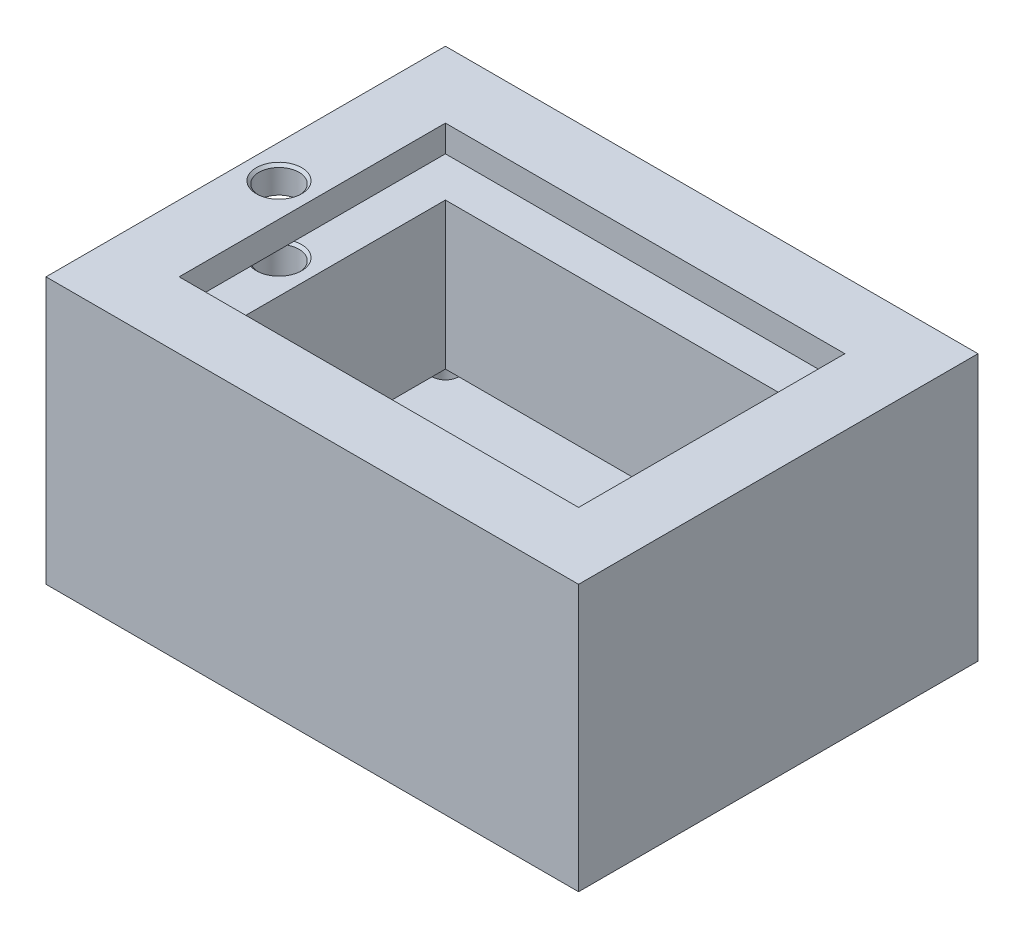
SolidWorks part; units mm, degrees
ref_plane "Front Plane" through (0, 0, 0) normal (0, 0, 1) x (1, 0, 0)
ref_plane "Top Plane" through (0, 0, 0) normal (0, 1, 0) x (1, 0, 0)
ref_plane "Right Plane" through (0, 0, 0) normal (1, 0, 0) x (0, 0, -1)
sketch "Sketch1" plane through (0, 0, 0) normal (0, 1, 0) x (1, 0, 0)
  line L1 (-25.4, -19.05) -> (25.4, -19.05)
  line L2 (-25.4, -19.05) -> (-25.4, 19.05)
  line L3 (-25.4, 19.05) -> (25.4, 19.05)
  line L4 (25.4, -19.05) -> (25.4, 19.05)
  line L5 (-25.4, -19.05) -> (25.4, 19.05) construction
  line L6 (-25.4, 19.05) -> (25.4, -19.05) construction
  point P0 (0, 0)
  dimension "D1" = 50.8
  dimension "D2" = 38.1
extrude "Boss-Extrude1" add sketch "Sketch1" along normal blind 25.4
sketch "Sketch2" plane through (0, 25.4, 0) normal (0, 1, 0) x (1, 0, 0)
  line L0 (25.4, 19.05) -> (-25.4, 19.05) construction
  line L1 (-19.05, -12.7) -> (19.05, -12.7)
  line L2 (-19.05, -12.7) -> (-19.05, 12.7)
  line L3 (-19.05, 12.7) -> (19.05, 12.7)
  line L4 (19.05, -12.7) -> (19.05, 12.7)
  line L5 (-19.05, -12.7) -> (19.05, 12.7) construction
  line L6 (-19.05, 12.7) -> (19.05, -12.7) construction
  line L8 (25.4, -19.05) -> (25.4, 19.05) construction
  point P0 (0, 0)
  dimension "D1" = 6.35
  dimension "D2" = 6.35
extrude "Cut-Extrude1" cut sketch "Sketch2" against normal blind 20.32
sketch "Sketch4" plane through (-25.4, 0, 0) normal (-1, 0, 0) x (0, 0, 1)
  line L0 (-16.5176, 22.86) -> (16.5176, 22.86)
  line L1 (16.5176, 22.86) -> (16.5176, 19.0424)
  line L2 (16.5176, 19.0424) -> (-16.5176, 19.0424)
  line L3 (-16.5176, 19.0424) -> (-16.5176, 22.86)
  line L5 (-19.05, 25.4) -> (19.05, 25.4) construction
  point P6 (0, 25.4)
  point P7 (0, 22.86)
  dimension "D1" = 33.0352
  dimension "D2" = 3.8176
  dimension "D3" = 2.54
extrude "Cut-Extrude2" cut sketch "Sketch4" against normal blind 48.2752
sketch "Sketch5" plane through (0, 25.4, 0) normal (0, 1, 0) x (1, 0, 0)
  line L0 (-19.05, 0) -> (-25.4, 0) construction
  line L1 (-19.05, 12.7) -> (-19.05, -12.7) construction
  line L2 (-25.4, 19.05) -> (-25.4, -19.05) construction
  circle A0 centre (-22.225, 0) radius 1.9088
  dimension "D1" = 3.8176
extrude "Cut-Extrude3" cut sketch "Sketch5" against normal blind 10.16
chamfer "Chamfer1" distance 0.254 angle 45 1 edges at (-22.225, 25.4, 1.9088)
chamfer "Chamfer2" distance 0.254 angle 45 1 edges at (-22.225, 19.0424, -1.9088)
sketch "Sketch15" plane through (0, 5.08, 0) normal (0, 1, 0) x (1, 0, 0)
  circle A0 centre (-19.05, 12.7) radius 1.27
  circle A1 centre (19.05, 12.7) radius 1.27
  circle A2 centre (-19.05, -12.7) radius 1.27
  circle A3 centre (19.05, -12.7) radius 1.27
  dimension "D1" = 2.54
  dimension "D2" = 2.54
  dimension "D3" = 2.54
  dimension "D4" = 2.54
extrude "Cut-Extrude4" cut sketch "Sketch15" against normal up to next
equation "\"L\"= 2'Box Length [in]"
equation "\"W\"= 1.5'Box Width [in]"
equation "\"D1@Sketch1\"=\"L\""
equation "\"D2@Sketch1\"=\"W\""
equation "\"H\"= 1'Box Height {in}"
equation "\"SW\"= 1.3 + 0.0006'Slide Width gap [in]"
equation "\"SL\"= 1.9 + 0.0006'Slide Length Gap [in]"
equation "\"D1@Sketch4\"=\"SW\""
equation "\"SH\"= 0.15 + 0.0003'Slide Height Gap [in]"
equation "\"D2@Sketch4\"=\"SH\""
equation "\"D1@Cut-Extrude2\"=\"SL\""
equation "\"Hole\"= 0.15 + 0.0003'Hole Radius [in]"
equation "\"D1@Sketch5\"=\"Hole\""
equation "\"Hole Depth\"= 0.4'Hole Depth [in]"
equation "\"D1@Cut-Extrude3\"=\"Hole Depth\""
